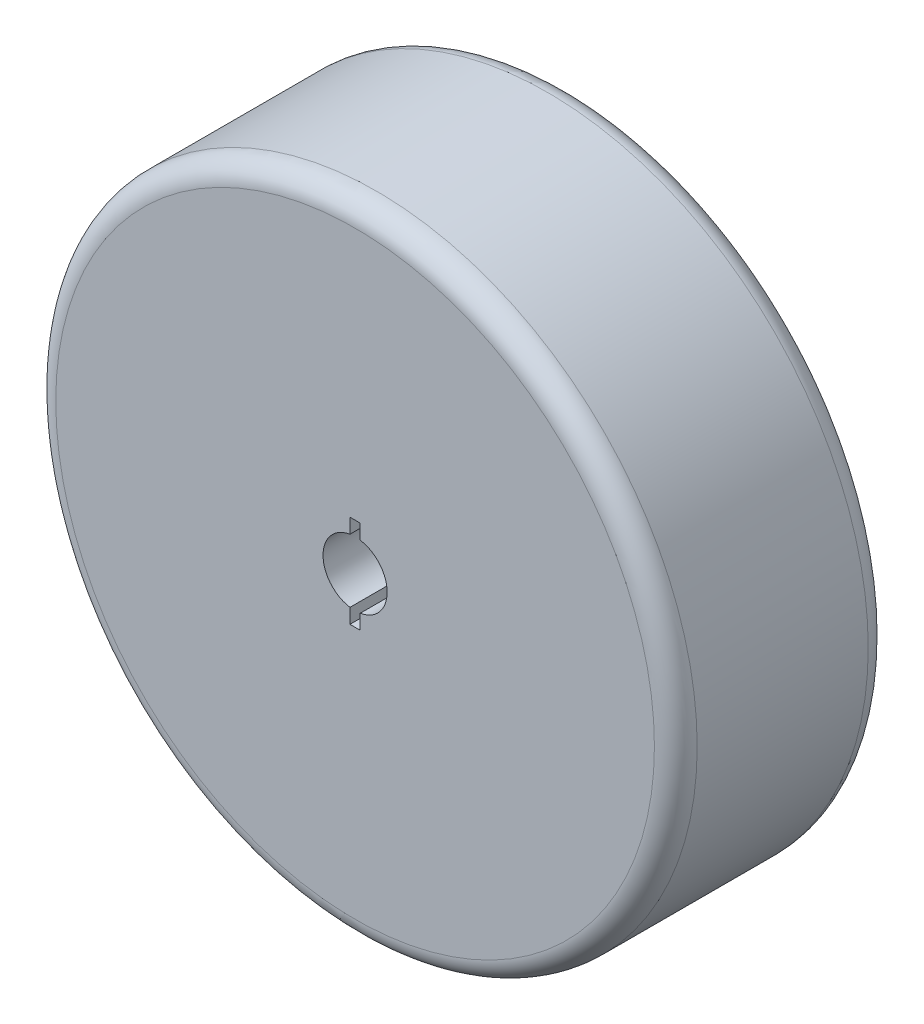
SolidWorks part; units mm, degrees
ref_plane "Front Plane" through (0, 0, 0) normal (0, 0, 1) x (1, 0, 0)
ref_plane "Top Plane" through (0, 0, 0) normal (0, 1, 0) x (1, 0, 0)
ref_plane "Right Plane" through (0, 0, 0) normal (1, 0, 0) x (0, 0, -1)
sketch "Sketch1" plane through (0, 0, 0) normal (0, 0, 1) x (1, 0, 0)
  circle A0 centre (0, 0) radius 38.1
extrude "Boss-Extrude1" add sketch "Sketch1" along normal blind 25.4
sketch "Sketch2" plane through (0, 0, 25.4) normal (0, 0, 1) x (1, 0, 0)
  circle A0 centre (0, 0) radius 3.81
  dimension "D1" = 7.62
extrude "Cut-Extrude1" cut sketch "Sketch2" against normal up to next
fillet "Fillet1" radius 2.54 1 edges at (38.1, 0, 25.4)
fillet "Fillet2" radius 2.54 1 edges at (38.1, 0, 0)
sketch "Sketch3" plane through (0, 0, 25.4) normal (0, 0, 1) x (1, 0, 0)
  line L1 (-0.6102, -5.5113) -> (0.6102, -5.5113)
  line L2 (-0.6102, -5.5113) -> (-0.6102, 5.5113)
  line L3 (-0.6102, 5.5113) -> (0.6102, 5.5113)
  line L4 (0.6102, -5.5113) -> (0.6102, 5.5113)
  line L5 (-0.6102, -5.5113) -> (0.6102, 5.5113) construction
  line L6 (-0.6102, 5.5113) -> (0.6102, -5.5113) construction
  point P0 (0, 0)
extrude "Cut-Extrude2" cut sketch "Sketch3" against normal up to next
